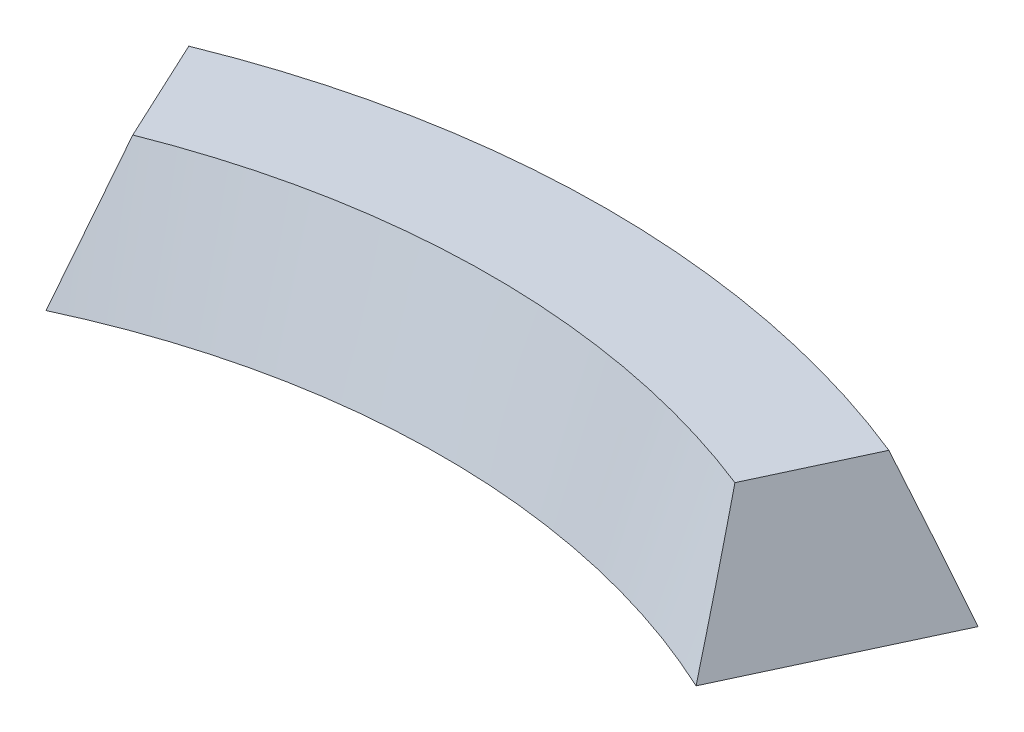
SolidWorks part; units mm, degrees
ref_plane "Front Plane" through (0, 0, 0) normal (0, 0, 1) x (1, 0, 0)
ref_plane "Top Plane" through (0, 0, 0) normal (0, 1, 0) x (1, 0, 0)
ref_plane "Right Plane" through (0, 0, 0) normal (1, 0, 0) x (0, 0, -1)
sketch "Sketch1" plane through (0, 0, 0) normal (0, 1, 0) x (1, 0, 0)
  line L2 (-11.666, 26.3171) -> (-15.0469, 33.5676)
  line L3 (12.8459, 26.3171) -> (16.2268, 33.5676)
  circle A2 centre (0, 0) radius 33 construction
  arc A5 (16.2268, 33.5676) -> (-15.0469, 33.5676) centre (0.59, 0.0342) ccw
  arc A6 (12.8459, 26.3171) -> (-11.666, 26.3171) centre (0.59, 0.0342) ccw
extrude "Boss-Extrude1" add sketch "Sketch1" along normal blind 5 draft 20
